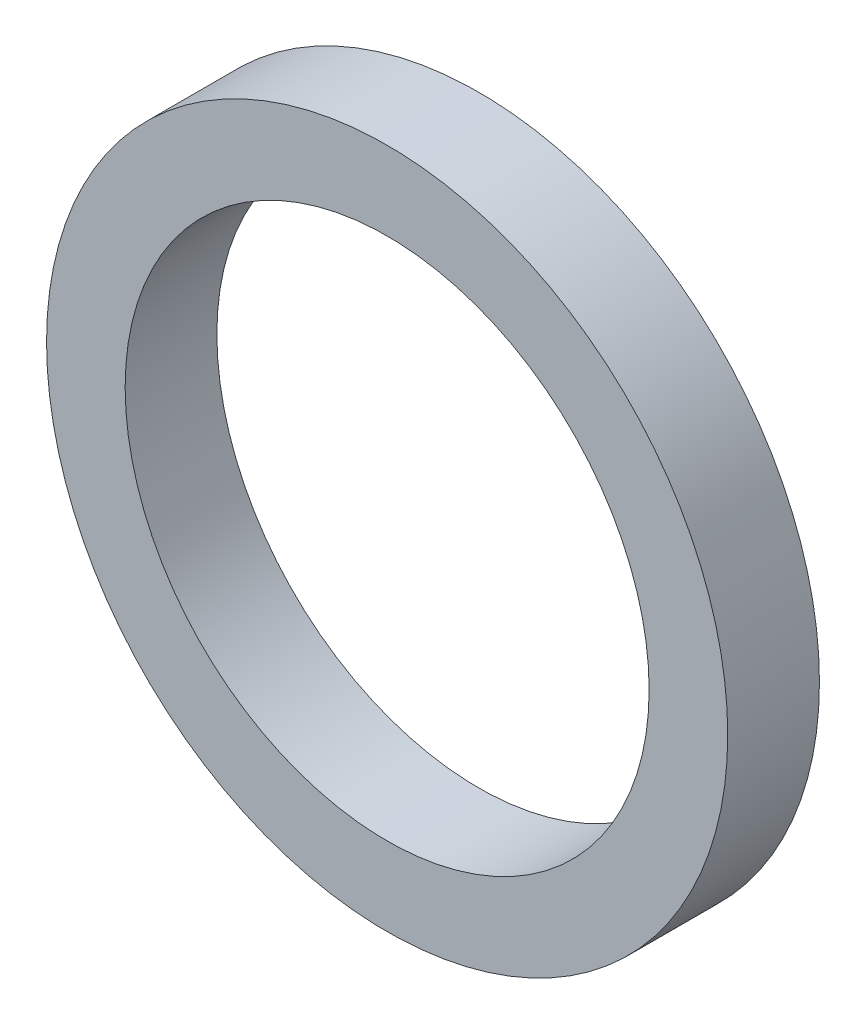
SolidWorks part; units mm, degrees
ref_plane "Front Plane" through (0, 0, 0) normal (0, 0, 1) x (1, 0, 0)
ref_plane "Top Plane" through (0, 0, 0) normal (0, 1, 0) x (1, 0, 0)
ref_plane "Right Plane" through (0, 0, 0) normal (1, 0, 0) x (0, 0, -1)
sketch "Sketch1" plane through (0, 0, 0) normal (0, 0, 1) x (1, 0, 0)
  circle A0 centre (0, 0) radius 20
  circle A1 centre (0, 0) radius 26
  dimension "D1" = 52
  dimension "D2" = 40
extrude "Boss-Extrude1" add sketch "Sketch1" along normal blind 7
